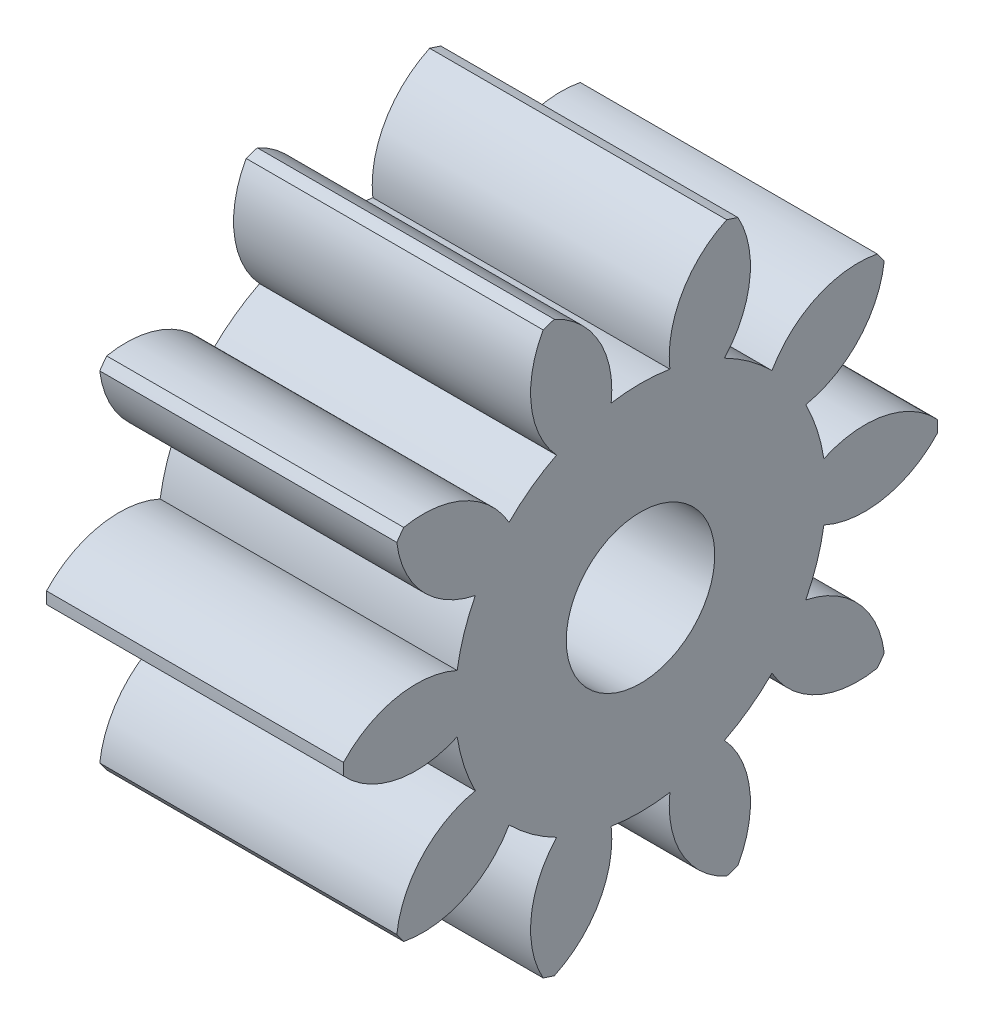
SolidWorks part; units mm, degrees
ref_plane "Plane1" through (0, 0, 0) normal (0, 0, 1) x (1, 0, 0)
ref_plane "Plane2" through (0, 0, 0) normal (0, 1, 0) x (1, 0, 0)
ref_plane "Plane3" through (0, 0, 0) normal (1, 0, 0) x (0, 0, -1)
other "Configuration Table"
sketch "HoldingSke" plane through (0, 0, 0) normal (0, 1, 0) x (1, 0, 0)
  line L0 (0, 0) -> (0.9848, -0.1736)
  line L1 (-15, 0) -> (100, 0) construction
  line L2 (0, 0) -> (-2.1039, 2.3779)
  line L3 (0, 0) -> (-11.863, 4.5341)
  line L4 (0, 0) -> (8.5048, 1.4996)
  line L5 (0, 0) -> (-46.8476, -17.4728)
  line L6 (0, 0) -> (-4.9738, -3.3558)
  line L7 (-2.1039, 2.3779) -> (8.6586, 51.2059)
  line L8 (-76.2, 54.61) -> (-75.7, 54.61)
  line L9 (-71.009, 38.7566) -> (-53.1078, 45.2721)
  line L10 (-76.2, 71.12) -> (104.1128, 71.12)
  line L11 (0, 0) -> (-6, 0)
  line L12 (-76.2, 101.6) -> (-76.162, 101.6)
  line L13 (24.9733, 27.94) -> (52.9518, 28.4284)
  line L14 (24.9733, 27.94) -> (24.9743, 27.94)
  line L15 (24.9733, 27.94) -> (100.4006, 29.5858)
  line L16 (-63.627, -1) -> (-12.827, -1)
  circle A0 centre (0, 0) radius 1.5
  circle A1 centre (0, 0) radius 3.749
  circle A2 centre (0, 0) radius 37.5
  circle A3 centre (0, 0) radius 1.5
  dimension "MHD" = 7.498
  dimension "Hub_dia" = 75
  dimension "Bore" = 3
  dimension "MBD" = 3
  dimension "Num_teeth" = 10
  dimension "Pitch" = 1
  dimension "Overall_len" = 50
  dimension "Show_teeth" = 10
  dimension "Thickness" = 6
  dimension "OAL" = 50.0001
  dimension "T_dim" = 0.5
  dimension "Ap" = 20
  dimension "H" = 19.05
  dimension "Pitch_radius" = 180.3128
  dimension "Width" = 6
  dimension "Backlash" = 0.038
  dimension "Addendum_fac" = 1
  dimension "Dedendum_fac" = 1.25
  dimension "Clearance_fac" = 0.25
  dimension "Dedendum_add" = 0.001
  dimension "Module" = 1
sketch "BasProSke" plane through (0, 0, 0) normal (0, 1, 0) x (1, 0, 0)
  line L0 (-10, 0) -> (60, 0) construction
  line L1 (0, 0) -> (0, 6)
  line L2 (0, 0) -> (6, 0)
  line L3 (6, 0) -> (6, 6)
  line L4 (6, 6) -> (0, 6)
  dimension "Thickness" = 6
  dimension "Diameter" = 12
revolve "Base-Revolve" add sketch "BasProSke" angle 360 about L0
sketch "TooCutSke" plane through (0, 0, 0) normal (1, 0, 0) x (0, 0, -1)
  line L1 (0, 0) -> (0, 107) construction
  line L2 (0, 0) -> (-0.8485, 4.9275) construction
  line L3 (0, 0) -> (-3.0584, 9.4126) construction
  line L4 (-0.8485, 4.9275) -> (-1.5292, 4.7063) construction
  arc A0 (0.5928, 3.7018) -> (-0.5928, 3.7018) centre (0, 0) ccw
  arc A1 (1.7758, 5.7578) -> (-1.7758, 5.7578) centre (0, 0) ccw
  circle A2 centre (0, 0) radius 5 construction
  circle A3 centre (0, 0) radius 4.6985 construction
  arc A4 (-0.5928, 3.7018) -> (-1.7758, 5.7578) centre (-2.5801, 3.9267) ccw
  arc A5 (1.7758, 5.7578) -> (0.5928, 3.7018) centre (2.5801, 3.9267) ccw
  dimension "Root_dia" = 7.498
  dimension "Overcut_dia" = 12.0508
  dimension "Pitch_dia" = 10
  dimension "Base_dia" = 9.3969
  dimension "Flank_rad" = 2
  dimension "Half_ang" = 18
  dimension "Half_CT" = 0.7157
extrude "ToothCut" cut sketch "TooCutSke" along normal through all
fillet "Breaks" [suppressed] radius 0.02
fillet "RootFillets" [suppressed] radius 0.251
pattern_circular "TeethCuts" count 10 every 36 about axis through (-10, 0, 0) along (1, 0, 0) of "ToothCut", "RootFillets", "Breaks"
sketch "HubNeaOneSke" plane through (0, 0, 0) normal (-1, 0, 0) x (0, 0, 1)
  circle A0 centre (0, 0) radius 3.749
  dimension "Diameter" = 7.498
extrude "HubNearOne" [suppressed] add sketch "HubNeaOneSke" along normal blind 44.0001
sketch "HubNeaBotSke" plane through (0, 0, 0) normal (-1, 0, 0) x (0, 0, 1)
  circle A0 centre (0, 0) radius 3.749
  dimension "Diameter" = 7.498
extrude "HubNearBoth" [suppressed] add sketch "HubNeaBotSke" along normal blind 22
ref_plane "FarPln" through (6, 0, 0) normal (1, 0, 0) x (0, 0, -1)
sketch "HubFarSke" plane through (6, 0, 0) normal (1, 0, 0) x (0, 0, -1)
  circle A0 centre (0, 0) radius 3.749
  dimension "Diameter" = 7.498
extrude "HubFar" [suppressed] add sketch "HubFarSke" along normal blind 22
sketch "BorSke" plane through (0, 0, 0) normal (1, 0, 0) x (0, 0, -1)
  circle A0 centre (0, 0) radius 1.5
  dimension "Diameter" = 3
extrude "Bore" cut sketch "BorSke" along normal mid plane 100.0001
sketch "KeySke" plane through (0, 0, 0) normal (1, 0, 0) x (0, 0, -1)
  line L0 (-0.6, 0) -> (-0.6, 2)
  line L1 (-0.6, 2) -> (0.6, 2)
  line L2 (0.6, 2) -> (0.6, 0)
  line L3 (0, 0) -> (0, 34) construction
  line L4 (-0.6, 0) -> (0.6, 0)
  dimension "Offset" = 2
  dimension "Width" = 1.2
extrude "Keyway" [suppressed] cut sketch "KeySke" along normal mid plane 100.0001
pattern_circular "Keyway2" [suppressed] count 2 every 90 about axis through (-10, 0, 0) along (1, 0, 0)
equation "' \"Module@HoldingSke\" = 6.35"
equation "' \"Num_teeth@HoldingSke\" = 12"
equation "' \"Ap@HoldingSke\" =  20"
equation "' \"Ap@HoldingSke\" = 20"
equation "' \"Width@HoldingSke\" = 0.5 * 25.4"
equation "' \"Hub_dia@HoldingSke\"= 1 * 25.4"
equation "' \"Hub_dia@HoldingSke\" = 1 * 25.4"
equation "' \"Overall_len@HoldingSke\" = 1.0 * 25.4"
equation "' \"Bore@HoldingSke\" = 0.75 * 25.4"
equation "' \"T_dim@HoldingSke\" = 0.1 * 25.4"
equation "' \"Width@KeySke\" = 0.25 * 25.4"
equation "' \"Show_teeth@HoldingSke\" = 13"
equation "' \"Backlash@HoldingSke\" = 0.009 * 25.4"
equation "' \"Addendum_fac@HoldingSke\" = 1.0"
equation "' \"Dedendum_fac@HoldingSke\" = 1.25"
equation "' \"Dedendum_add@HoldingSke\" = 0.00005 * 25.4"
equation "' \"Clearance_fac@HoldingSke\" = 0.25"
equation "\"Pitch@HoldingSke\" = 1 / \"Module@HoldingSke\""
equation "\"Overcut_dia@TooCutSke\" = (\"Num_teeth@HoldingSke\" + 2 * \"Addendum_fac@HoldingSke\") / \"Pitch@HoldingSke\" + 0.002 * 25.4"
equation "\"Pitch_dia@TooCutSke\" = \"Num_teeth@HoldingSke\" / \"Pitch@HoldingSke\""
equation "\"Base_dia@TooCutSke\" = \"Num_teeth@HoldingSke\" / \"Pitch@HoldingSke\" * cos((\"Ap@HoldingSke\"  * 3.14159265 / 180))"
equation "\"Root_dia@TooCutSke\" = (\"Num_teeth@HoldingSke\" + 2) / \"Pitch@HoldingSke\" - 2 * (\"Addendum_fac@HoldingSke\" + \"Dedendum_fac@HoldingSke\") / \"Pitch@HoldingSke\" - \"Dedendum_add@HoldingSke\" * 2"
equation "\"Half_ang@TooCutSke\" = 180 / \"Num_teeth@HoldingSke\""
equation "\"Half_CT@TooCutSke\" = \"Num_teeth@HoldingSke\" / \"Pitch@HoldingSke\" * sin((3.14159265 / 2 / \"Num_teeth@HoldingSke\")) / 2 - 7 * \"Backlash@HoldingSke\" / 4"
equation "\"Flank_rad@TooCutSke\" = \"Num_teeth@HoldingSke\" / \"Pitch@HoldingSke\" / 5"
equation "\"Radius@RootFillets\" = \"Clearance_fac@HoldingSke\" / \"Pitch@HoldingSke\" + \"Dedendum_add@HoldingSke\""
equation "\"Break_rad@Breaks\" = 0.02 / \"Pitch@HoldingSke\""
equation "\"Thickness@HoldingSke\" = \"Width@HoldingSke\""
equation "\"OAL@HoldingSke\" = \"Thickness@HoldingSke\""
equation "\"MHD@HoldingSke\" = (\"Num_teeth@HoldingSke\" + 2) / \"Pitch@HoldingSke\" - 2 * (\"Addendum_fac@HoldingSke\" + \"Dedendum_fac@HoldingSke\")  / \"Pitch@HoldingSke\" - \"Dedendum_add@HoldingSke\" * 2"
equation "\"MBD@HoldingSke\" = (\"Num_teeth@HoldingSke\" + 2) / \"Pitch@HoldingSke\" - 2 * (\"Addendum_fac@HoldingSke\" + \"Dedendum_fac@HoldingSke\")  / \"Pitch@HoldingSke\" - \"Dedendum_add@HoldingSke\" * 2 - 0.002 * 25.4"
equation "\"MHD@HoldingSke\" = ((sgn( \"MHD@HoldingSke\" - \"Hub_dia@HoldingSke\" )-1)*( \"MHD@HoldingSke\" - \"Hub_dia@HoldingSke\" ))/-2+ \"Hub_dia@HoldingSke\""
equation "\"MBD@HoldingSke\" = ((sgn( \"MBD@HoldingSke\" - \"Bore@HoldingSke\" )-1)*( \"MBD@HoldingSke\" - \"Bore@HoldingSke\" ))/-2+ \"Bore@HoldingSke\""
equation "\"OAL@HoldingSke\" = ((sgn( \"OAL@HoldingSke\" - \"Overall_len@HoldingSke\" )+1)*( \"OAL@HoldingSke\" - \"Overall_len@HoldingSke\" ))/2 + \"Overall_len@HoldingSke\" + 0.000002 * 25.4"
equation "\"Num_teeth@TeethCuts\" = int( \"Show_teeth@HoldingSke\" ) + 1"
equation "\"Num_teeth@TeethCuts\" = ((sgn( \"Num_teeth@TeethCuts\" - \"Num_teeth@HoldingSke\" )-1)*( \"Num_teeth@TeethCuts\" - \"Num_teeth@HoldingSke\" ))/-2+ \"Num_teeth@HoldingSke\""
equation "\"Num_teeth@TeethCuts\" = ((sgn( \"Num_teeth@TeethCuts\" - 2.0)+1)*( \"Num_teeth@TeethCuts\" - 2.0))/2 +2.0"
equation "\"Angle@TeethCuts\" = 360.0 / \"Num_teeth@HoldingSke\""
equation "\"Diameter@BasProSke\" = (\"Num_teeth@HoldingSke\" + 2 * \"Addendum_fac@HoldingSke\") / \"Pitch@HoldingSke\""
equation "\"Thickness@BasProSke\"  = \"Thickness@HoldingSke\""
equation "' \"Fillet_rad@BasProSke\" =  \"Thickness@HoldingSke\" * 0.05"
equation "' \"Fillet_rad@BasProSke\" = \"Thickness@HoldingSke\" * 0.05"
equation "\"MHD@HoldingSke\" = ((sgn( \"MHD@HoldingSke\" - \"Root_dia@TooCutSke\" )-1)*( \"MHD@HoldingSke\" - \"Root_dia@TooCutSke\" ))/-2+ \"Root_dia@TooCutSke\""
equation "\"Diameter@HubNeaOneSke\" = \"MHD@HoldingSke\""
equation "\"Length@HubNearOne\" = \"OAL@HoldingSke\" - \"Thickness@BasProSke\""
equation "\"Diameter@HubNeaBotSke\" = \"MHD@HoldingSke\""
equation "\"Length@HubNearBoth\" = ( \"OAL@HoldingSke\" - \"Thickness@BasProSke\" ) / 2.0"
equation "\"Thickness@FarPln\" = \"Thickness@BasProSke\""
equation "\"Diameter@HubFarSke\" = \"MHD@HoldingSke\""
equation "\"Length@HubFar\" = ( \"OAL@HoldingSke\" - \"Thickness@BasProSke\" ) / 2.0"
equation "\"Diameter@BorSke\" = \"MBD@HoldingSke\""
equation "\"D1@Bore\" = \"OAL@HoldingSke\" * 2.0"
equation "\"D1@Keyway\" = \"OAL@HoldingSke\" * 2.0"
equation "\"Offset@KeySke\" = \"T_dim@HoldingSke\" + \"MBD@HoldingSke\" / 2.0"
